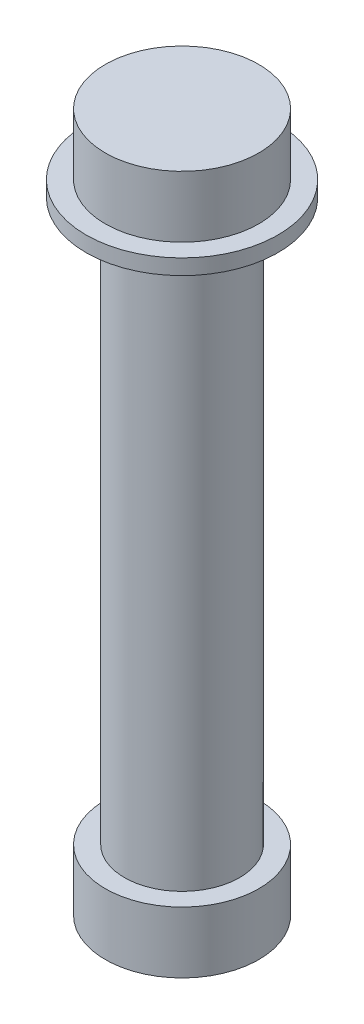
SolidWorks part; units mm, degrees
ref_plane "Front Plane" through (0, 0, 0) normal (0, 0, 1) x (1, 0, 0)
ref_plane "Top Plane" through (0, 0, 0) normal (0, 1, 0) x (1, 0, 0)
ref_plane "Right Plane" through (0, 0, 0) normal (1, 0, 0) x (0, 0, -1)
sketch "Sketch1" plane through (0, 0, 0) normal (0, 1, 0) x (1, 0, 0)
  circle A0 centre (0, 0) radius 4.7625
  dimension "D1" = 9.525
extrude "Boss-Extrude1" add sketch "Sketch1" along normal blind 46.355
sketch "Sketch2" plane through (0, 46.355, 0) normal (0, 1, 0) x (1, 0, 0)
  circle A0 centre (0, 0) radius 7.9375
  dimension "D1" = 15.875
extrude "Boss-Extrude2" add sketch "Sketch2" along normal blind 1.27
sketch "Sketch3" plane through (0, 0, 0) normal (0, -1, 0) x (1, 0, 0)
  circle A0 centre (0, 0) radius 6.35
  dimension "D1" = 12.7
extrude "Boss-Extrude3" add sketch "Sketch3" along normal blind 5.08
sketch "Sketch4" plane through (0, 47.625, 0) normal (0, 1, 0) x (1, 0, 0)
  circle A0 centre (0, 0) radius 6.35
  dimension "D1" = 12.7
extrude "Boss-Extrude4" add sketch "Sketch4" along normal blind 5.08
